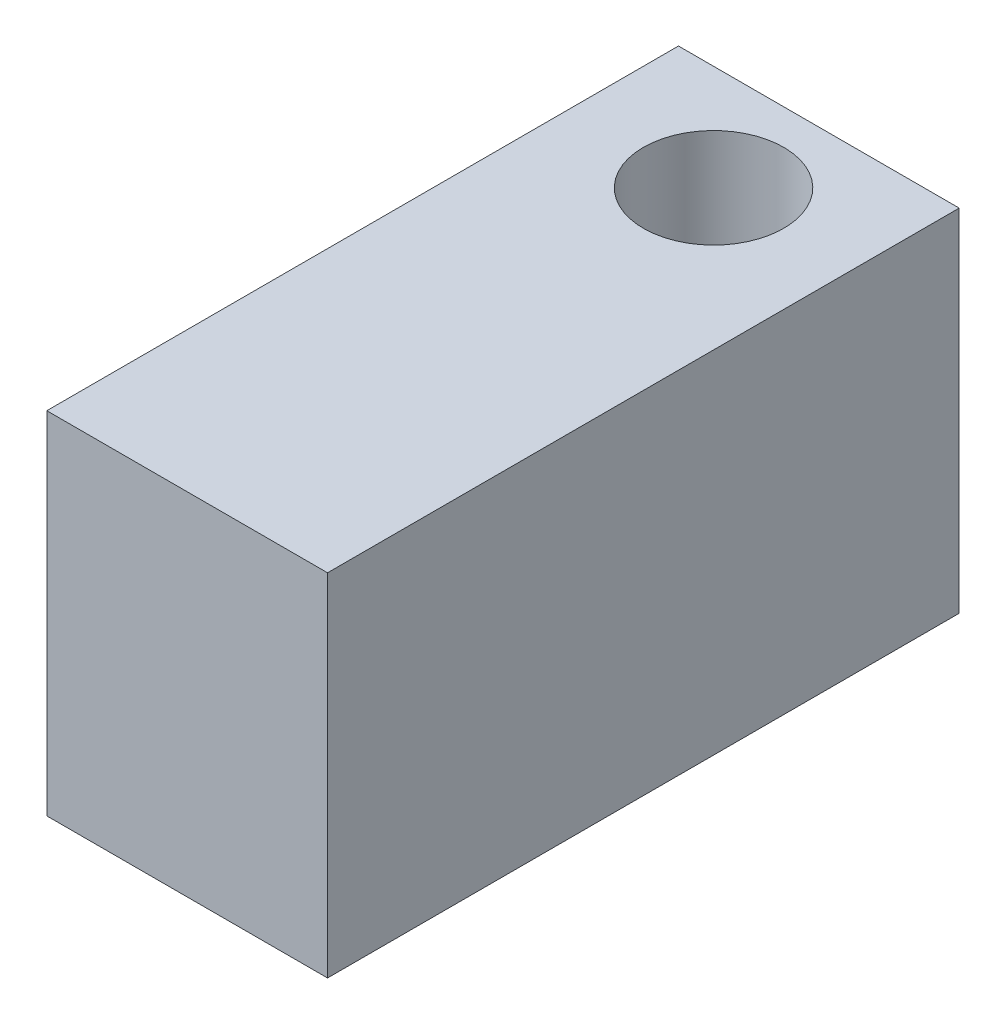
SolidWorks part; units mm, degrees
ref_plane "Front Plane" through (0, 0, 0) normal (0, 0, 1) x (1, 0, 0)
ref_plane "Top Plane" through (0, 0, 0) normal (0, 1, 0) x (1, 0, 0)
ref_plane "Right Plane" through (0, 0, 0) normal (1, 0, 0) x (0, 0, -1)
sketch "Sketch1" plane through (0, 0, 0) normal (0, 0, 1) x (1, 0, 0)
  line L1 (20, -25) -> (-20, -25)
  line L2 (20, -25) -> (20, 25)
  line L3 (20, 25) -> (-20, 25)
  line L4 (-20, -25) -> (-20, 25)
  line L5 (20, -25) -> (-20, 25) construction
  line L6 (20, 25) -> (-20, -25) construction
  point P0 (0, 0)
  dimension "D1" = 40
  dimension "D2" = 50
extrude "Boss-Extrude1" add sketch "Sketch1" along normal blind 90
sketch "Sketch2" plane through (0, 25, 0) normal (0, 1, 0) x (1, 0, 0)
  line L0 (0, 0) -> (0, -90) construction
  line L1 (20, -90) -> (-20, -90) construction
  line L2 (20, 0) -> (-20, 0) construction
  circle A0 centre (0, -15) radius 10
  dimension "D1" = 20
  dimension "D2" = 15
extrude "Cut-Extrude1" cut sketch "Sketch2" against normal up to next
